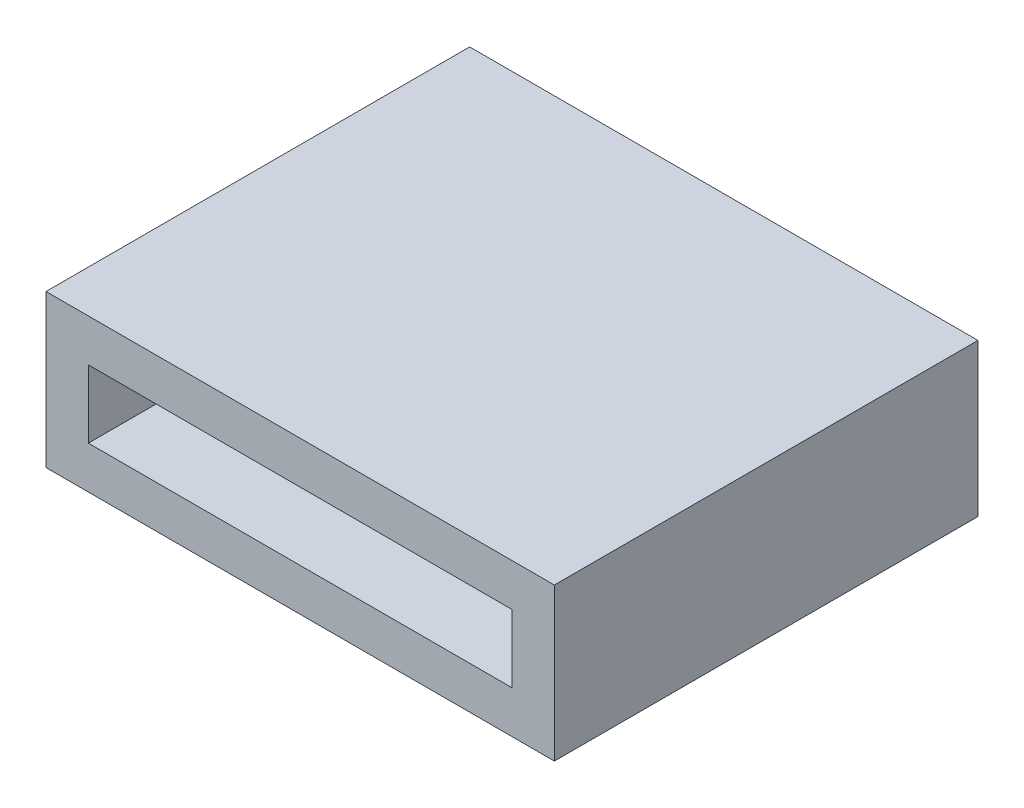
SolidWorks part; units mm, degrees
ref_plane "정면" through (0, 0, 0) normal (0, 0, 1) x (1, 0, 0)
ref_plane "윗면" through (0, 0, 0) normal (0, 1, 0) x (1, 0, 0)
ref_plane "우측면" through (0, 0, 0) normal (1, 0, 0) x (0, 0, -1)
sketch "스케치1" plane through (0, 0, 0) normal (0, 0, 1) x (1, 0, 0)
  line L0 (-5, -5) -> (-5, 13)
  line L1 (0, 0) -> (50, 0)
  line L2 (0, 0) -> (0, 8)
  line L3 (0, 8) -> (50, 8)
  line L4 (50, 0) -> (50, 8)
  line L5 (-5, 13) -> (55, 13)
  line L6 (55, -5) -> (55, 13)
  line L7 (-5, -5) -> (55, -5)
  dimension "D2" = 8
  dimension "D3" = 50
  dimension "D1" = 5
extrude "보스-돌출1" add sketch "스케치1" along normal blind 50
ref_plane "평면1" through (0, 0, 25) normal (0, 0, 1) x (1, 0, 0)
sketch "스케치2" plane through (0, 0, 25) normal (0, 0, 1) x (1, 0, 0)
  line L1 (0, 8) -> (50, 8)
  line L2 (0, 8) -> (0, 0)
  line L3 (0, 0) -> (50, 0)
  line L4 (50, 8) -> (50, 0)
extrude "보스-돌출2" add sketch "스케치2" along normal mid plane 1
